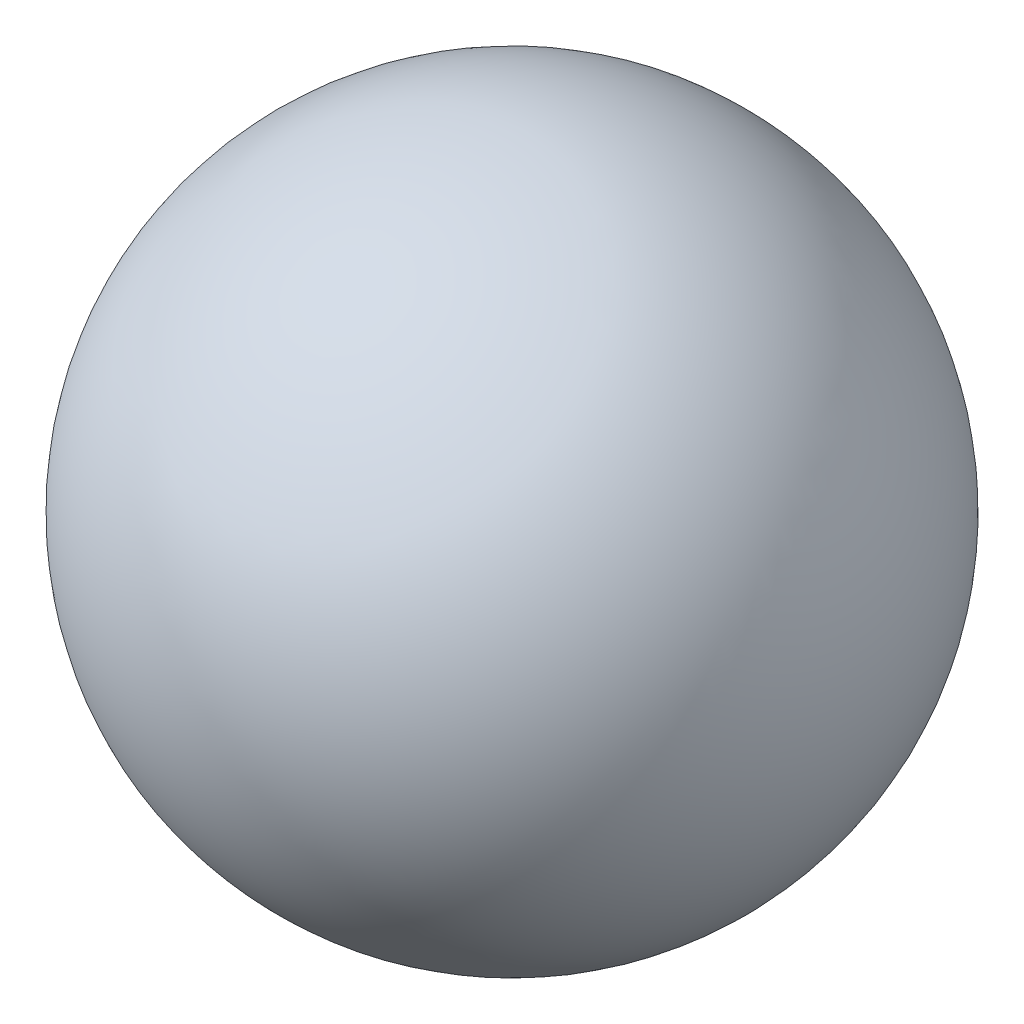
SolidWorks part; units mm, degrees
ref_plane "Front Plane" through (0, 0, 0) normal (0, 0, 1) x (1, 0, 0)
ref_plane "Top Plane" through (0, 0, 0) normal (0, 1, 0) x (1, 0, 0)
ref_plane "Right Plane" through (0, 0, 0) normal (1, 0, 0) x (0, 0, -1)
sketch "Sketch1" plane through (0, 0, 0) normal (0, 0, 1) x (1, 0, 0)
  line L0 (-1.605, -2.7799) -> (-2.3638, -4.0941)
  line L1 (-1.5101, -2.6157) -> (-2.4078, -4.1704) construction
  arc A0 (-2.3638, -4.0941) -> (-1.605, -2.7799) centre (-1.9844, -3.437) ccw
revolve "Revolve1" add sketch "Sketch1" angle 360 about L1
